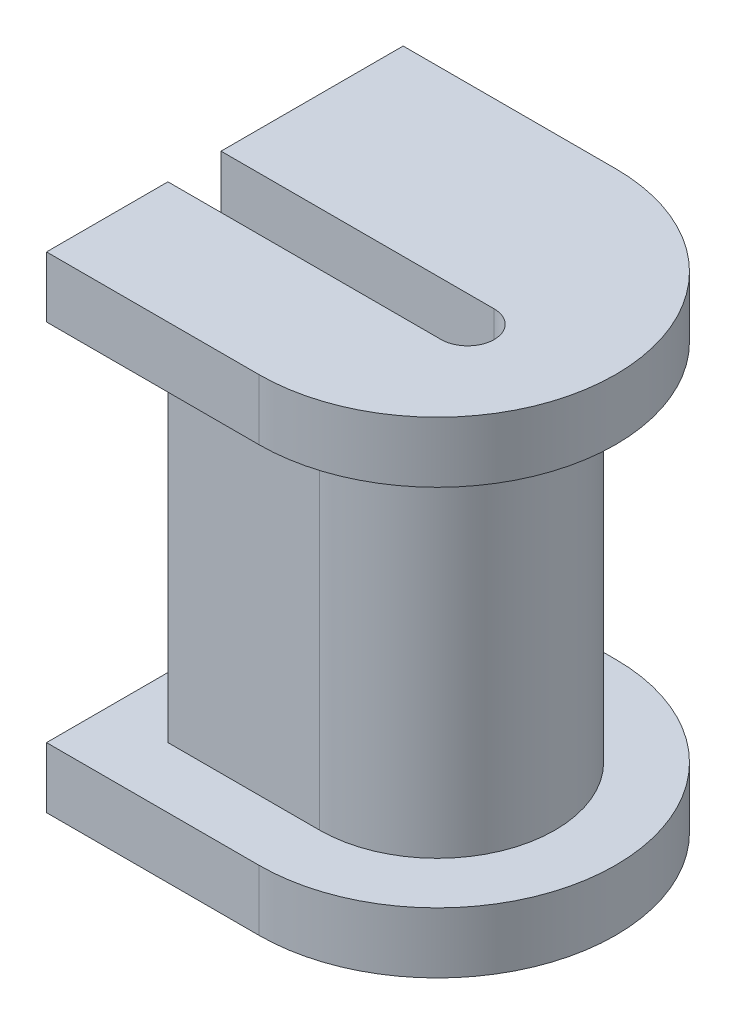
SolidWorks part; units mm, degrees
ref_plane "Front Plane" through (0, 0, 0) normal (0, 0, 1) x (1, 0, 0)
ref_plane "Top Plane" through (0, 0, 0) normal (0, 1, 0) x (1, 0, 0)
ref_plane "Right Plane" through (0, 0, 0) normal (1, 0, 0) x (0, 0, -1)
sketch "Sketch1" plane through (0, 0, 0) normal (0, 1, 0) x (1, 0, 0)
  line L0 (0, 0) -> (7, 0)
  line L1 (7, -1.75) -> (0, -1.75)
  line L2 (0, -1.75) -> (0, -3.75)
  line L3 (0, -3.75) -> (5, -3.75)
  line L4 (5, 4) -> (0, 4)
  line L5 (0, 4) -> (0, 0)
  arc A0 (7, 0) -> (7, -1.75) centre (7, -0.875) cw
  arc A1 (5, -3.75) -> (5, 4) centre (5, 0.125) ccw
  dimension "D1" = 1.75
  dimension "D2" = 2
  dimension "D3" = 4
  dimension "D4" = 2
  dimension "D5" = 5
extrude "Boss-Extrude1" add sketch "Sketch1" along normal mid plane 12
sketch "Sketch2" plane through (0, 6, 0) normal (0, 1, 0) x (1, 0, 0)
  line L7 (7, -1.75) -> (0, -1.75) construction
  line L9 (0, 0) -> (7, 0) construction
  line L10 (5, 6) -> (-2, 6)
  line L11 (-2, 6) -> (-2, 0)
  line L12 (5, 6) -> (-2, 6)
  line L13 (-2, -1.75) -> (-2, -5.75)
  line L14 (-2, -5.75) -> (5, -5.75)
  line L15 (-2, -1.75) -> (-2, -5.75)
  line L16 (-2, -5.75) -> (5, -5.75)
  line L17 (-2, 6) -> (-2, 0)
  line L18 (7, -1.75) -> (-2, -1.75)
  line L19 (-2, 0) -> (7, 0)
  arc A1 (7, -1.75) -> (7, 0) centre (7, -0.875) ccw construction
  arc A2 (5, -5.75) -> (5, 6) centre (5, 0.125) ccw
  arc A3 (5, -5.75) -> (5, 6) centre (5, 0.125) ccw
  arc A4 (7, -1.75) -> (7, 0) centre (7, -0.875) ccw
  dimension "D1" = 2
  dimension "D2" = 2
extrude "Boss-Extrude2" add sketch "Sketch2" along normal blind 2
mirror "Mirror1" about plane through (0, 0, 0) normal (0, 1, 0) of "Boss-Extrude2"
